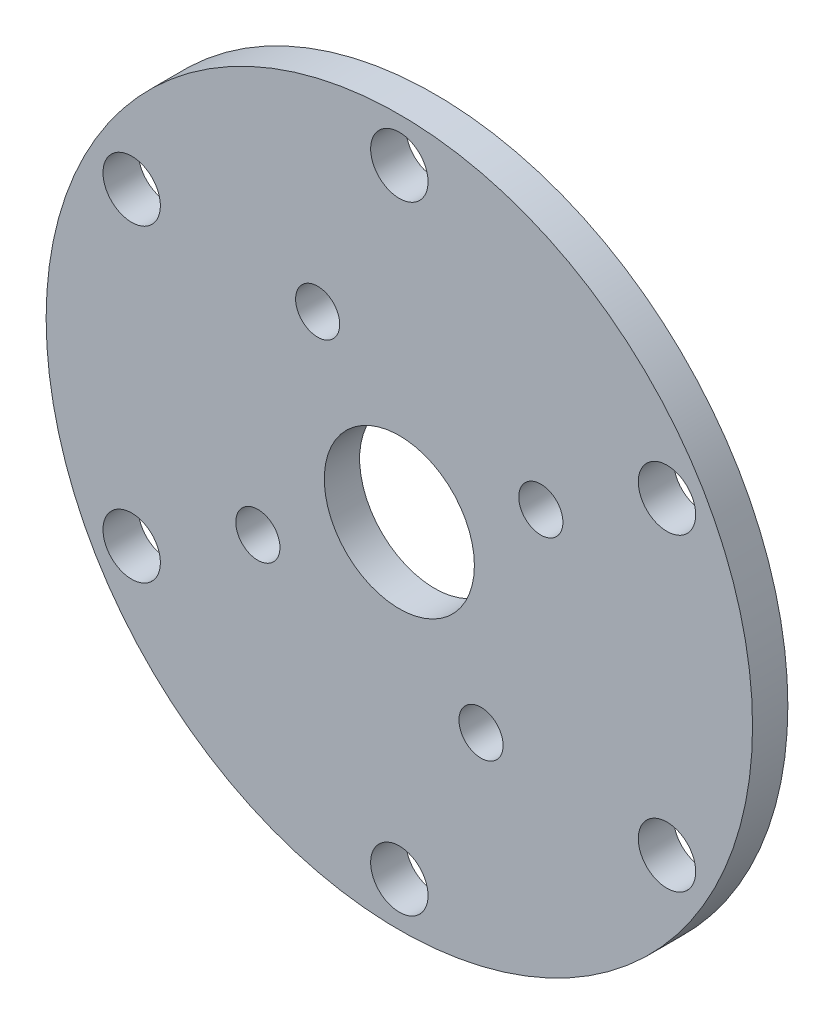
SolidWorks part; units mm, degrees
ref_plane "前视基准面" through (0, 0, 0) normal (0, 0, 1) x (1, 0, 0)
ref_plane "上视基准面" through (0, 0, 0) normal (0, 1, 0) x (1, 0, 0)
ref_plane "右视基准面" through (0, 0, 0) normal (1, 0, 0) x (0, 0, -1)
sketch "草图1" plane through (0, 0, 0) normal (0, 0, 1) x (1, 0, 0)
  line L0 (0, 35) -> (0, 0)
  line L1 (0, 0) -> (-30.3109, 17.5)
  line L2 (0, 0) -> (-9.25, 16.0215)
  circle A0 centre (0, 0) radius 40
  circle A2 centre (0, 35) radius 3.25
  circle A3 centre (30.3109, 17.5) radius 3.25
  circle A4 centre (30.3109, -17.5) radius 3.25
  circle A5 centre (0, -35) radius 3.25
  circle A6 centre (-30.3109, -17.5) radius 3.25
  circle A7 centre (-30.3109, 17.5) radius 3.25
  circle A8 centre (0, 0) radius 8.5
  circle A9 centre (0, 0) radius 18.5
  circle A10 centre (-9.25, 16.0215) radius 2.5
  circle A11 centre (16.0215, 9.25) radius 2.5
  circle A12 centre (9.25, -16.0215) radius 2.5
  circle A13 centre (-16.0215, -9.25) radius 2.5
  dimension "D1" = 6
  dimension "D2" = 150
  dimension "D3" = 4
  dimension "D4" = 37
extrude "凸台-拉伸1" add sketch "草图1" along normal blind 4
